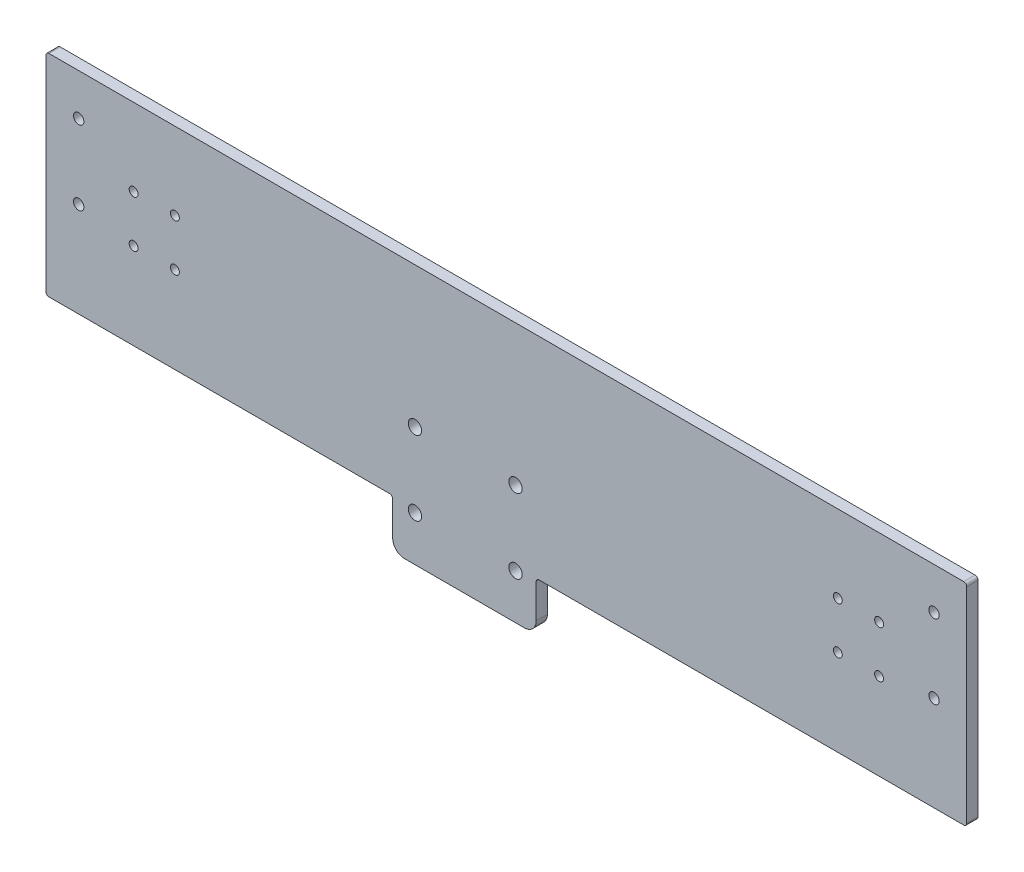
SolidWorks part; units mm, degrees
ref_plane "Front Plane" through (0, 0, 0) normal (0, 0, 1) x (1, 0, 0)
ref_plane "Top Plane" through (0, 0, 0) normal (0, 1, 0) x (1, 0, 0)
ref_plane "Right Plane" through (0, 0, 0) normal (1, 0, 0) x (0, 0, -1)
sketch "Sketch1" plane through (0, 0, 0) normal (0, 0, 1) x (1, 0, 0)
  line L0 (1372.8138, -10.0019) -> (155.0398, -10.0019) construction
  line L1 (299, -10.0019) -> (156.0398, -10.0019)
  line L2 (300, -9.0019) -> (300, 60)
  line L3 (299, 61) -> (-9, 61)
  line L4 (-10, -9.0019) -> (-10, 60)
  line L5 (174.7365, -39.8966) -> (178.5805, -39.8966) construction
  line L7 (106.724, -11.0019) -> (106.724, -22.4585)
  line L8 (110.724, -26.4585) -> (151.0398, -26.4585)
  line L9 (155.0398, -11.0019) -> (155.0398, -22.4585)
  line L10 (105.724, -10.0019) -> (-9, -10.0019)
  line L11 (106.724, -10.0019) -> (-9.6787, -10.0019) construction
  line L12 (145, 59.9472) -> (145, 95.2858) construction
  line L14 (3.4865, 61) -> (9.5, 61) construction
  arc A0 (105.724, -10.0019) -> (106.724, -11.0019) centre (105.724, -11.0019) cw
  arc A1 (156.0398, -10.0019) -> (155.0398, -11.0019) centre (156.0398, -11.0019) ccw
  arc A10 (299, -10.0019) -> (300, -9.0019) centre (299, -9.0019) ccw
  arc A11 (300, 60) -> (299, 61) centre (299, 60) ccw
  arc A12 (-9, 61) -> (-10, 60) centre (-9, 60) ccw
  arc A13 (-9, -10.0019) -> (-10, -9.0019) centre (-9, -9.0019) cw
  circle A22 centre (289, 22.0015) radius 1.75
  circle A30 centre (289, 47.0015) radius 1.75
  circle A42 centre (148.0828, -11.3161) radius 2.25
  circle A43 centre (148.0828, 13.6839) radius 2.25
  circle A44 centre (114.2249, 13.6839) radius 2.25
  circle A45 centre (114.2249, -11.3161) radius 2.25
  circle A46 centre (256.6, 19.1472) radius 1.5
  circle A47 centre (270.5, 19.1472) radius 1.5
  circle A48 centre (270.5, 34.9472) radius 1.5
  circle A49 centre (256.6, 34.9472) radius 1.5
  circle A50 centre (33.4, 34.9472) radius 1.5
  circle A51 centre (19.5, 34.9472) radius 1.5
  circle A52 centre (19.5, 19.1472) radius 1.5
  circle A53 centre (33.4, 19.1472) radius 1.5
  circle A54 centre (1, 47.0015) radius 1.75
  circle A55 centre (1, 22.0015) radius 1.75
  arc A56 (151.0398, -26.4585) -> (155.0398, -22.4585) centre (151.0398, -22.4585) ccw
  arc A57 (106.724, -22.4585) -> (110.724, -26.4585) centre (110.724, -22.4585) ccw
  dimension "D3" = 1
  dimension "D4" = 1
  dimension "D5" = 4
  dimension "D2" = 310
extrude "Boss-Extrude1" add sketch "Sketch1" along normal blind 3.8
